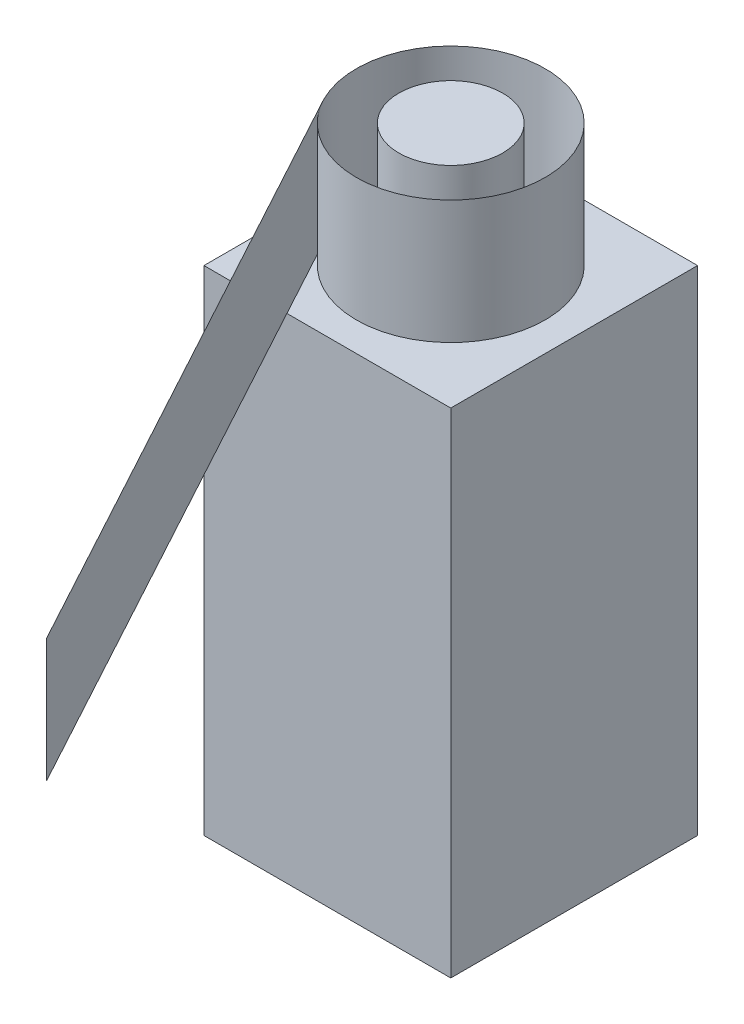
SolidWorks part; units mm, degrees
ref_plane "Front Plane" through (0, 0, 0) normal (0, 0, 1) x (1, 0, 0)
ref_plane "Top Plane" through (0, 0, 0) normal (0, 1, 0) x (1, 0, 0)
ref_plane "Right Plane" through (0, 0, 0) normal (1, 0, 0) x (0, 0, -1)
sketch "Sketch1" plane through (0, 0, 0) normal (0, 1, 0) x (1, 0, 0)
  line L1 (5, 5) -> (-5, 5)
  line L2 (5, 5) -> (5, -5)
  line L3 (5, -5) -> (-5, -5)
  line L4 (-5, 5) -> (-5, -5)
  line L5 (5, 5) -> (-5, -5) construction
  line L6 (5, -5) -> (-5, 5) construction
  point P0 (0, 0)
  dimension "D1" = 10
  dimension "D2" = 10
extrude "Boss-Extrude1" add sketch "Sketch1" along normal blind 20
sketch "Sketch2" plane through (0, 20, 0) normal (0, 1, 0) x (1, 0, 0)
  circle A0 centre (0, 0) radius 2.1038
extrude "Boss-Extrude2" add sketch "Sketch2" along normal blind 5
sketch "Sketch3" plane through (0, 20, 0) normal (0, 1, 0) x (1, 0, 0)
  line L0 (-3.3618, -1.8225) -> (9.8976, -26.2805)
  circle A0 centre (0, 0) radius 3.824
  spline S0 degree 3 poles (-0.1191, -33.9239) (0.0974, -35.0964) (1.1685, -33.9392) (0.0925, -32.4881) (-1.1226, -33.1573) (-1.4893, -34.1503) (-0.9549, -34.8371) (-0.4799, -35.5444) (0.6826, -35.5719) (1.9919, -34.5899) (1.5416, -32.6611) (0.0932, -31.5445) (-0.8792, -32.2027) (-1.5227, -32.6253) (-2.0005, -33.3909) (-1.9176, -34.3928) (-1.409, -35.5435) (-0.2409, -36.8246) (1.4907, -36.2295) (3.2609, -34.8768) (2.198, -32.4037) (0.9716, -29.6611) (-1.6992, -30.6264) (-2.8755, -32.0391) (-2.87, -33.7102) (-2.2742, -35.2631) (-1.3644, -37.0743) (1.2293, -37.9172) (3.732, -35.8629) (3.5235, -32.6391) (2.0055, -30.7997) (0.9508, -28.0149) (-1.2443, -29.0925) (-2.8169, -30.0785) (-4.1671, -31.5627) (-3.8823, -33.2916) (-3.2173, -34.9073) (-2.3195, -36.5725) (-1.0343, -38.3118) (1.1059, -38.9498) (3.3265, -38.0884) (4.0138, -36.1374) (4.6122, -34.4114) (4.4774, -32.1852) (3.7858, -30.362) (2.2495, -28.8571) (0.5978, -27.7891) (-1.4042, -28.2466) (-2.898, -28.7809) (-4.3602, -29.5418) (-5.1922, -30.7256) (-5.5889, -32.1256) (-5.113, -33.6759) (-4.2467, -35.5249) (-3.0437, -37.5884) (-1.2285, -39.6426) (1.1962, -39.4719) (3.2938, -39.1685) (5.6116, -38.0545) (5.5789, -35.734) (6.2281, -33.8223) (5.8624, -31.7779) (4.8128, -29.6513) (3.5396, -27.5915) (1.0717, -26.8054) (-1.7307, -26.4417) (-4.1295, -28.0959) (-6.1115, -29.6171) (-7.001, -31.285) (-7.3863, -33.023) (-6.8304, -34.8565) (-5.5887, -36.7748) (-4.2062, -39.0912) (-1.7481, -40.809) (1.0772, -41.4893) (3.4768, -40.1013) (5.267, -39.0809) (7.6022, -37.5653) (6.9133, -34.6329) (7.3569, -31.8222) (5.6292, -29.4361) (4.2551, -26.7851) (0.9815, -26.1731) (-2.1528, -25.6195) (-4.7896, -27.8956) (-7.6221, -29.2675) (-8.5367, -32.7016) (-7.823, -36.4299) (-5.9014, -40.2482) (-2.7863, -43.2578) (1.2616, -43.3555) (4.7661, -42.5068) (7.9409, -40.2689) (8.9993, -37.2385) (8.7852, -34.4906) (8.9091, -32.0487) (6.6943, -28.5356) (4.4365, -24.024) (-1.147, -23.0518) (-5.2942, -24.0059) (-8.583, -26.4866) (-10.0464, -29.6663) (-10.1317, -32.883) (-10.2884, -35.9127) (-8.8809, -38.5618) (-7.6028, -41.1224) (-5.1158, -43.2736) (-1.7491, -43.8158) (1.6037, -45.5045) (5.6414, -44.4181) (9.375, -42.3799) (10.1184, -38.8096) (10.828, -36.1212) (10.4575, -33.7496) (10.2711, -31.619) (9.8354, -29.3152) (8.6892, -27.0192) (7.0275, -25.0873) (5.2845, -23.0916) (2.7245, -22.2278) (0.147, -21.2226) (-3.4219, -21.7148) (-7.9062, -23.5049) (-12.2761, -28.7804) (-13.2566, -36.7489) (-8.4625, -44.8087) (2.2862, -48.0525) (16.1814, -38.1261) (11.1543, -23.4787) (2.8672, -21.7859) knots 0 0 0 0 0.004413 0.00784 0.011136 0.013757 0.015532 0.018062 0.02045 0.024321 0.02992 0.034565 0.03626 0.03914 0.041078 0.043418 0.047108 0.05183 0.055734 0.061148 0.068071 0.075545 0.082641 0.086723 0.090452 0.095792 0.100722 0.106725 0.115814 0.122476 0.131222 0.137032 0.142255 0.147405 0.154022 0.156531 0.161554 0.168625 0.172316 0.17928 0.185599 0.189886 0.19588 0.200804 0.208212 0.211378 0.218826 0.223059 0.227877 0.232222 0.236495 0.239568 0.244023 0.249527 0.256654 0.264295 0.270354 0.27553 0.2827 0.288683 0.293201 0.299573 0.305133 0.313302 0.318428 0.326211 0.335907 0.341427 0.346989 0.35127 0.35593 0.36244 0.370423 0.378051 0.387149 0.392512 0.400366 0.405124 0.413772 0.421894 0.428322 0.437541 0.44515 0.454849 0.462344 0.473007 0.479569 0.490179 0.504098 0.515122 0.52392 0.536404 0.544957 0.555168 0.561256 0.568127 0.574837 0.595386 0.60628 0.619197 0.630193 0.639383 0.647238 0.657038 0.663935 0.671789 0.680982 0.689855 0.699929 0.71101 0.723363 0.7327 0.739941 0.746503 0.752389 0.757853 0.765956 0.773379 0.779193 0.787637 0.795398 0.801886 0.817039 0.834799 0.856285 0.879795 0.907161 0.940171 1 1 1 1 construction
surface "Surface-Extrude1" sketch "Sketch3" parameters "D1"=5
